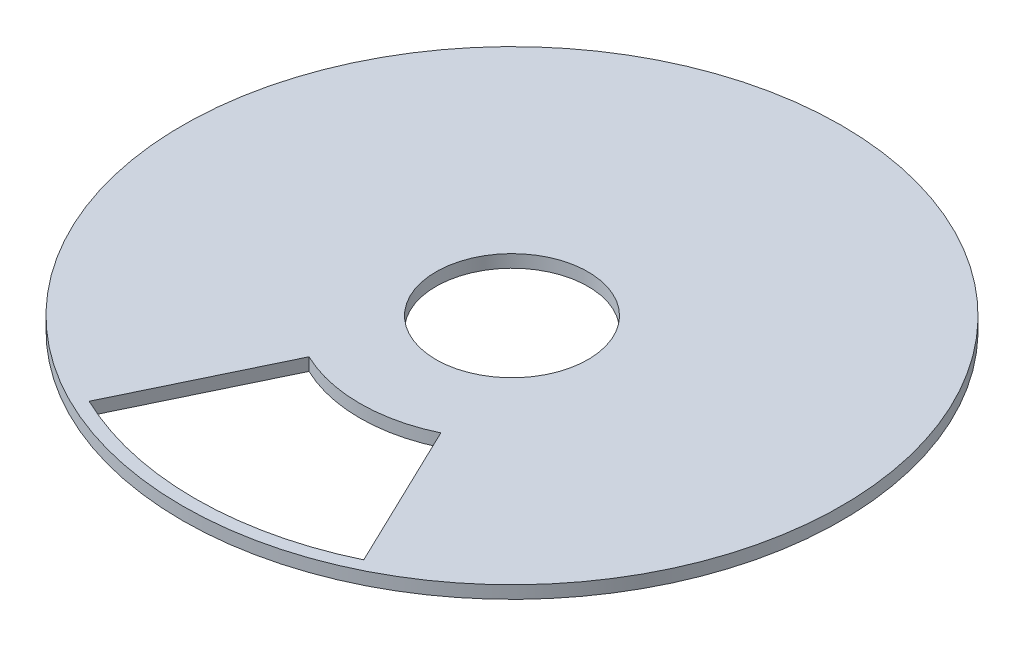
SolidWorks part; units mm, degrees
material "1060 Alloy"
ref_plane "Front Plane" through (0, 0, 0) normal (0, 0, 1) x (1, 0, 0)
ref_plane "Top Plane" through (0, 0, 0) normal (0, 1, 0) x (1, 0, 0)
ref_plane "Right Plane" through (0, 0, 0) normal (1, 0, 0) x (0, 0, -1)
sketch "Sketch1" plane through (0, 0, 0) normal (0, 1, 0) x (1, 0, 0)
  circle A0 centre (0, 0) radius 165.1
  dimension "D1" = 330.2
extrude "Boss-Extrude1" add sketch "Sketch1" along normal blind 6.35
sketch "Sketch2" plane through (0, 6.35, 0) normal (0, 1, 0) x (1, 0, 0)
  circle A0 centre (0, 0) radius 38.1
  dimension "D1" = 76.2
extrude "Cut-Extrude1" cut sketch "Sketch2" against normal blind 6.35
sketch "Sketch3" plane through (0, 6.35, 0) normal (0, 1, 0) x (1, 0, 0)
  line L0 (-33.02, -68.674) -> (-68.7917, -143.0709)
  line L1 (33.02, -68.674) -> (68.7917, -143.0709)
  line L2 (0, 0) -> (33.02, -68.674) construction
  line L3 (0, 0) -> (-33.02, -68.674) construction
  arc A0 (-33.02, -68.674) -> (33.02, -68.674) centre (0, 0) ccw
  arc A1 (-68.7917, -143.0709) -> (68.7917, -143.0709) centre (0, 0) ccw
  circle A3 centre (0, 0) radius 165.1 construction
  dimension "D1" = 152.4
  dimension "D2" = 6.35
  dimension "D3" = 66.04
extrude "Cut-Extrude2" cut sketch "Sketch3" against normal blind 6.35
